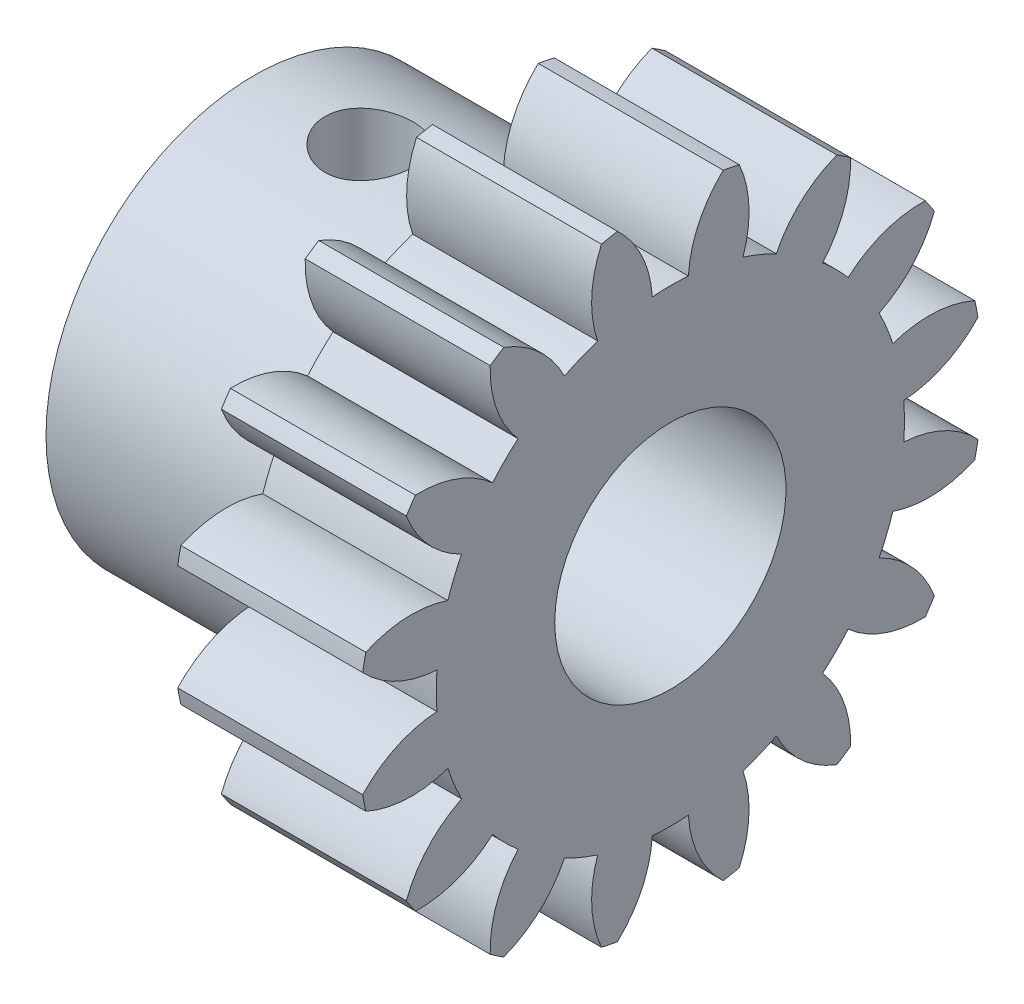
SolidWorks part; units mm, degrees
ref_plane "Plane1" through (0, 0, 0) normal (0, 0, 1) x (1, 0, 0)
ref_plane "Plane2" through (0, 0, 0) normal (0, 1, 0) x (1, 0, 0)
ref_plane "Plane3" through (0, 0, 0) normal (1, 0, 0) x (0, 0, -1)
sketch "HoldingSke" plane through (0, 0, 0) normal (0, 1, 0) x (1, 0, 0)
  line L0 (0, 0) -> (0.6408, -0.1838)
  line L1 (-15, 0) -> (100, 0) construction
  line L2 (0, 0) -> (-2.1039, 2.3779)
  line L3 (0, 0) -> (-11.863, 4.5341)
  line L4 (0, 0) -> (8.3015, 2.3804)
  line L5 (0, 0) -> (-16.8652, -6.2902)
  line L6 (0, 0) -> (-6.6317, -4.4744)
  line L7 (-2.1039, 2.3779) -> (1.7706, 19.956)
  line L8 (-76.2, 54.61) -> (-74.4, 54.61)
  line L9 (-71.009, 38.7566) -> (-53.1078, 45.2721)
  line L10 (-76.2, 71.12) -> (104.1128, 71.12)
  line L11 (0, 0) -> (-8, 0)
  line L12 (-76.2, 101.6) -> (-76.147, 101.6)
  line L13 (24.9733, 27.94) -> (52.9518, 28.4284)
  line L14 (24.9733, 27.94) -> (24.9743, 27.94)
  line L15 (24.9733, 27.94) -> (100.4006, 29.5858)
  line L16 (-63.627, -1.5) -> (-12.827, -1.5)
  circle A0 centre (0, 0) radius 5
  circle A1 centre (0, 0) radius 9
  circle A2 centre (0, 0) radius 9
  circle A3 centre (0, 0) radius 5
  dimension "MHD" = 18
  dimension "Hub_dia" = 18
  dimension "Bore" = 10
  dimension "MBD" = 10
  dimension "Num_teeth" = 16
  dimension "Pitch" = 0.6667
  dimension "Overall_len" = 18
  dimension "Show_teeth" = 16
  dimension "Thickness" = 8
  dimension "OAL" = 18.0001
  dimension "T_dim" = 1.8
  dimension "Ap" = 20
  dimension "H" = 19.05
  dimension "Pitch_radius" = 180.3128
  dimension "Width" = 8
  dimension "Backlash" = 0.053
  dimension "Addendum_fac" = 1
  dimension "Dedendum_fac" = 1.25
  dimension "Clearance_fac" = 0.25
  dimension "Dedendum_add" = 0.001
  dimension "Module" = 1.5
sketch "BasProSke" plane through (0, 0, 0) normal (0, 1, 0) x (1, 0, 0)
  line L0 (-10, 0) -> (60, 0) construction
  line L1 (0, 0) -> (0, 13.5)
  line L2 (0, 0) -> (8, 0)
  line L3 (8, 0) -> (8, 13.5)
  line L4 (8, 13.5) -> (0, 13.5)
  dimension "Thickness" = 8
  dimension "Diameter" = 27
revolve "Base-Revolve" add sketch "BasProSke" angle 360 about L0
sketch "TooCutSke" plane through (0, 0, 0) normal (1, 0, 0) x (0, 0, -1)
  line L1 (0, 0) -> (0, 107) construction
  line L2 (0, 0) -> (-1.2689, 11.9327) construction
  line L3 (0, 0) -> (-4.663, 23.4427) construction
  line L4 (-1.2689, 11.9327) -> (-2.3315, 11.7214) construction
  arc A0 (0.7798, 10.0939) -> (-0.7798, 10.0939) centre (0, 0) ccw
  arc A1 (2.3105, 13.3266) -> (-2.3105, 13.3266) centre (0, 0) ccw
  circle A2 centre (0, 0) radius 12 construction
  circle A3 centre (0, 0) radius 11.2763 construction
  arc A4 (-0.7798, 10.0939) -> (-2.3105, 13.3266) centre (-5.571, 9.804) ccw
  arc A5 (2.3105, 13.3266) -> (0.7798, 10.0939) centre (5.571, 9.804) ccw
  dimension "Root_dia" = 20.248
  dimension "Overcut_dia" = 27.0508
  dimension "Pitch_dia" = 24
  dimension "Base_dia" = 22.5526
  dimension "Flank_rad" = 4.8
  dimension "Half_ang" = 11.25
  dimension "Half_CT" = 1.0835
extrude "ToothCut" cut sketch "TooCutSke" along normal through all
fillet "Breaks" [suppressed] radius 0.03
fillet "RootFillets" [suppressed] radius 0.376
pattern_circular "TeethCuts" count 16 every 22.5 about axis through (-10, 0, 0) along (1, 0, 0) of "ToothCut", "RootFillets", "Breaks"
sketch "HubNeaOneSke" plane through (0, 0, 0) normal (-1, 0, 0) x (0, 0, 1)
  circle A0 centre (0, 0) radius 9
  dimension "Diameter" = 18
extrude "HubNearOne" add sketch "HubNeaOneSke" along normal blind 10.0001
sketch "HubNeaBotSke" plane through (0, 0, 0) normal (-1, 0, 0) x (0, 0, 1)
  circle A0 centre (0, 0) radius 9
  dimension "Diameter" = 18
extrude "HubNearBoth" [suppressed] add sketch "HubNeaBotSke" along normal blind 5
ref_plane "FarPln" through (8, 0, 0) normal (1, 0, 0) x (0, 0, -1)
sketch "HubFarSke" plane through (8, 0, 0) normal (1, 0, 0) x (0, 0, -1)
  circle A0 centre (0, 0) radius 9
  dimension "Diameter" = 18
extrude "HubFar" [suppressed] add sketch "HubFarSke" along normal blind 5
sketch "BorSke" plane through (0, 0, 0) normal (1, 0, 0) x (0, 0, -1)
  circle A0 centre (0, 0) radius 5
  dimension "Diameter" = 10
extrude "Bore" cut sketch "BorSke" along normal mid plane 36.0001
sketch "KeySke" plane through (0, 0, 0) normal (1, 0, 0) x (0, 0, -1)
  line L0 (-2, 0) -> (-2, 6.8)
  line L1 (-2, 6.8) -> (2, 6.8)
  line L2 (2, 6.8) -> (2, 0)
  line L3 (0, 0) -> (0, 34) construction
  line L4 (-2, 0) -> (2, 0)
  dimension "Offset" = 6.8
  dimension "Width" = 4
extrude "Keyway" [suppressed] cut sketch "KeySke" along normal mid plane 36.0001
pattern_circular "Keyway2" [suppressed] count 2 every 90 about axis through (-10, 0, 0) along (1, 0, 0)
sketch "草图1" plane through (0, 0, 0) normal (0, 1, 0) x (1, 0, 0)
  circle A0 centre (-5.0285, 0) radius 1.9
  dimension "D1" = 3.8
extrude "切除-拉伸1" cut sketch "草图1" against normal through all both and the other way through all
equation "' \"Module@HoldingSke\" = 6.35"
equation "' \"Num_teeth@HoldingSke\" = 12"
equation "' \"Ap@HoldingSke\" =  20"
equation "' \"Ap@HoldingSke\" = 20"
equation "' \"Width@HoldingSke\" = 0.5 * 25.4"
equation "' \"Hub_dia@HoldingSke\"= 1 * 25.4"
equation "' \"Hub_dia@HoldingSke\" = 1 * 25.4"
equation "' \"Overall_len@HoldingSke\" = 1.0 * 25.4"
equation "' \"Bore@HoldingSke\" = 0.75 * 25.4"
equation "' \"T_dim@HoldingSke\" = 0.1 * 25.4"
equation "' \"Width@KeySke\" = 0.25 * 25.4"
equation "' \"Show_teeth@HoldingSke\" = 13"
equation "' \"Backlash@HoldingSke\" = 0.009 * 25.4"
equation "' \"Addendum_fac@HoldingSke\" = 1.0"
equation "' \"Dedendum_fac@HoldingSke\" = 1.25"
equation "' \"Dedendum_add@HoldingSke\" = 0.00005 * 25.4"
equation "' \"Clearance_fac@HoldingSke\" = 0.25"
equation "\"Pitch@HoldingSke\" = 1 / \"Module@HoldingSke\""
equation "\"Overcut_dia@TooCutSke\" = (\"Num_teeth@HoldingSke\" + 2 * \"Addendum_fac@HoldingSke\") / \"Pitch@HoldingSke\" + 0.002 * 25.4"
equation "\"Pitch_dia@TooCutSke\" = \"Num_teeth@HoldingSke\" / \"Pitch@HoldingSke\""
equation "\"Base_dia@TooCutSke\" = \"Num_teeth@HoldingSke\" / \"Pitch@HoldingSke\" * cos((\"Ap@HoldingSke\"  * 3.14159265 / 180))"
equation "\"Root_dia@TooCutSke\" = (\"Num_teeth@HoldingSke\" + 2) / \"Pitch@HoldingSke\" - 2 * (\"Addendum_fac@HoldingSke\" + \"Dedendum_fac@HoldingSke\") / \"Pitch@HoldingSke\" - \"Dedendum_add@HoldingSke\" * 2"
equation "\"Half_ang@TooCutSke\" = 180 / \"Num_teeth@HoldingSke\""
equation "\"Half_CT@TooCutSke\" = \"Num_teeth@HoldingSke\" / \"Pitch@HoldingSke\" * sin((3.14159265 / 2 / \"Num_teeth@HoldingSke\")) / 2 - 7 * \"Backlash@HoldingSke\" / 4"
equation "\"Flank_rad@TooCutSke\" = \"Num_teeth@HoldingSke\" / \"Pitch@HoldingSke\" / 5"
equation "\"Radius@RootFillets\" = \"Clearance_fac@HoldingSke\" / \"Pitch@HoldingSke\" + \"Dedendum_add@HoldingSke\""
equation "\"Break_rad@Breaks\" = 0.02 / \"Pitch@HoldingSke\""
equation "\"Thickness@HoldingSke\" = \"Width@HoldingSke\""
equation "\"OAL@HoldingSke\" = \"Thickness@HoldingSke\""
equation "\"MHD@HoldingSke\" = (\"Num_teeth@HoldingSke\" + 2) / \"Pitch@HoldingSke\" - 2 * (\"Addendum_fac@HoldingSke\" + \"Dedendum_fac@HoldingSke\")  / \"Pitch@HoldingSke\" - \"Dedendum_add@HoldingSke\" * 2"
equation "\"MBD@HoldingSke\" = (\"Num_teeth@HoldingSke\" + 2) / \"Pitch@HoldingSke\" - 2 * (\"Addendum_fac@HoldingSke\" + \"Dedendum_fac@HoldingSke\")  / \"Pitch@HoldingSke\" - \"Dedendum_add@HoldingSke\" * 2 - 0.002 * 25.4"
equation "\"MHD@HoldingSke\" = ((sgn( \"MHD@HoldingSke\" - \"Hub_dia@HoldingSke\" )-1)*( \"MHD@HoldingSke\" - \"Hub_dia@HoldingSke\" ))/-2+ \"Hub_dia@HoldingSke\""
equation "\"MBD@HoldingSke\" = ((sgn( \"MBD@HoldingSke\" - \"Bore@HoldingSke\" )-1)*( \"MBD@HoldingSke\" - \"Bore@HoldingSke\" ))/-2+ \"Bore@HoldingSke\""
equation "\"OAL@HoldingSke\" = ((sgn( \"OAL@HoldingSke\" - \"Overall_len@HoldingSke\" )+1)*( \"OAL@HoldingSke\" - \"Overall_len@HoldingSke\" ))/2 + \"Overall_len@HoldingSke\" + 0.000002 * 25.4"
equation "\"Num_teeth@TeethCuts\" = int( \"Show_teeth@HoldingSke\" ) + 1"
equation "\"Num_teeth@TeethCuts\" = ((sgn( \"Num_teeth@TeethCuts\" - \"Num_teeth@HoldingSke\" )-1)*( \"Num_teeth@TeethCuts\" - \"Num_teeth@HoldingSke\" ))/-2+ \"Num_teeth@HoldingSke\""
equation "\"Num_teeth@TeethCuts\" = ((sgn( \"Num_teeth@TeethCuts\" - 2.0)+1)*( \"Num_teeth@TeethCuts\" - 2.0))/2 +2.0"
equation "\"Angle@TeethCuts\" = 360.0 / \"Num_teeth@HoldingSke\""
equation "\"Diameter@BasProSke\" = (\"Num_teeth@HoldingSke\" + 2 * \"Addendum_fac@HoldingSke\") / \"Pitch@HoldingSke\""
equation "\"Thickness@BasProSke\"  = \"Thickness@HoldingSke\""
equation "' \"Fillet_rad@BasProSke\" =  \"Thickness@HoldingSke\" * 0.05"
equation "' \"Fillet_rad@BasProSke\" = \"Thickness@HoldingSke\" * 0.05"
equation "\"MHD@HoldingSke\" = ((sgn( \"MHD@HoldingSke\" - \"Root_dia@TooCutSke\" )-1)*( \"MHD@HoldingSke\" - \"Root_dia@TooCutSke\" ))/-2+ \"Root_dia@TooCutSke\""
equation "\"Diameter@HubNeaOneSke\" = \"MHD@HoldingSke\""
equation "\"Length@HubNearOne\" = \"OAL@HoldingSke\" - \"Thickness@BasProSke\""
equation "\"Diameter@HubNeaBotSke\" = \"MHD@HoldingSke\""
equation "\"Length@HubNearBoth\" = ( \"OAL@HoldingSke\" - \"Thickness@BasProSke\" ) / 2.0"
equation "\"Thickness@FarPln\" = \"Thickness@BasProSke\""
equation "\"Diameter@HubFarSke\" = \"MHD@HoldingSke\""
equation "\"Length@HubFar\" = ( \"OAL@HoldingSke\" - \"Thickness@BasProSke\" ) / 2.0"
equation "\"Diameter@BorSke\" = \"MBD@HoldingSke\""
equation "\"D1@Bore\" = \"OAL@HoldingSke\" * 2.0"
equation "\"D1@Keyway\" = \"OAL@HoldingSke\" * 2.0"
equation "\"Offset@KeySke\" = \"T_dim@HoldingSke\" + \"MBD@HoldingSke\" / 2.0"
